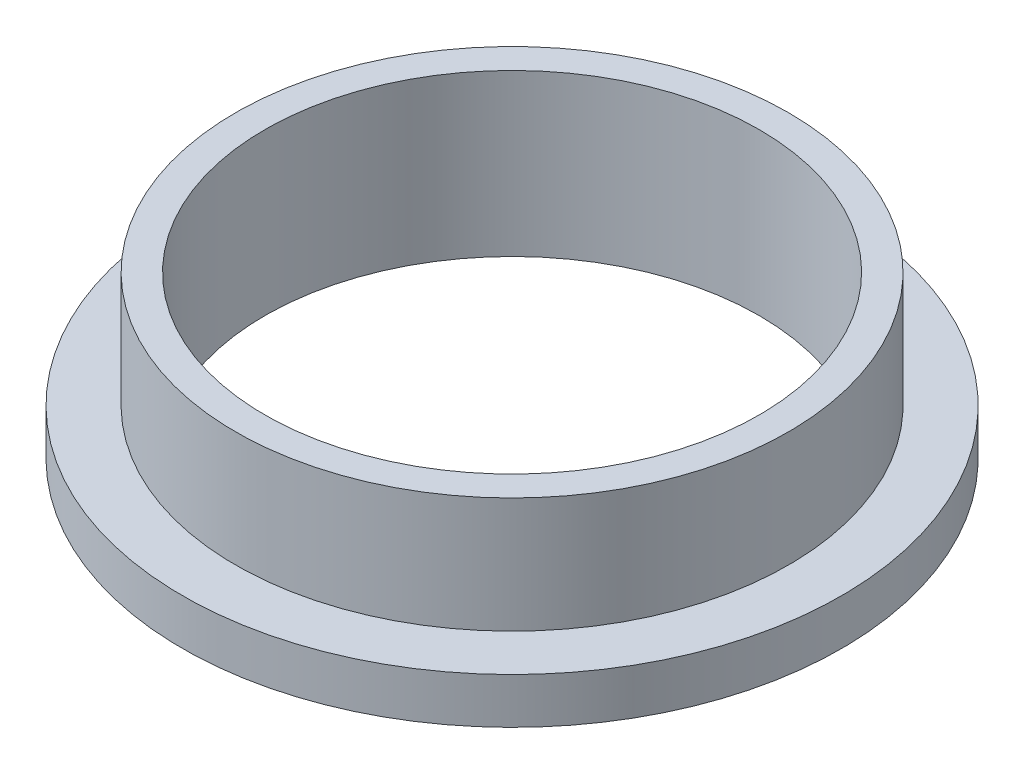
SolidWorks part; units mm, degrees
ref_plane "Front Plane" through (0, 0, 0) normal (0, 0, 1) x (1, 0, 0)
ref_plane "Top Plane" through (0, 0, 0) normal (0, 1, 0) x (1, 0, 0)
ref_plane "Right Plane" through (0, 0, 0) normal (1, 0, 0) x (0, 0, -1)
sketch "Sketch1" plane through (0, 0, 0) normal (1, 0, 0) x (0, 0, -1)
  line L0 (6.75, 0) -> (6.75, 4.4)
  line L1 (6.75, 4.4) -> (7.55, 4.4)
  line L2 (7.55, 4.4) -> (7.55, 1.25)
  line L3 (7.55, 1.25) -> (9, 1.25)
  line L4 (9, 1.25) -> (9, 0)
  line L5 (9, 0) -> (6.75, 0)
  line L6 (0, 0) -> (0, 4.6559) construction
  dimension "D1" = 9
  dimension "D2" = 1.25
  dimension "D3" = 6.75
  dimension "D4" = 0.8
  dimension "D5" = 4.4
revolve "Revolve1" add sketch "Sketch1" angle 360 about L6
